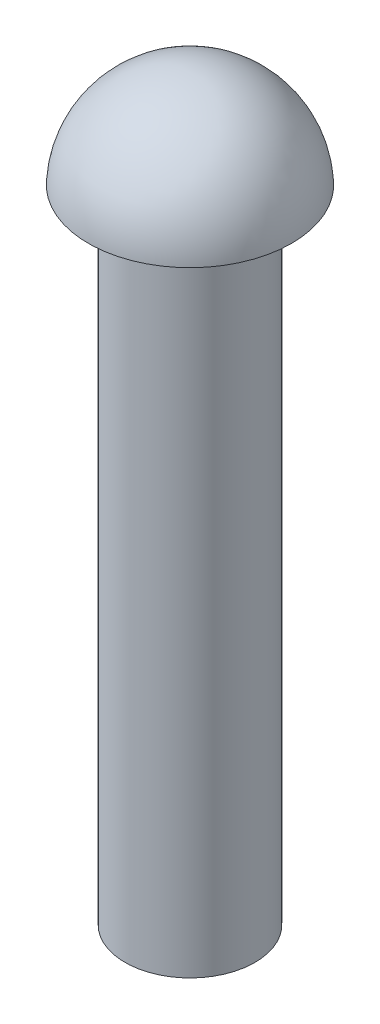
SolidWorks part; units mm, degrees
material "2.0060 (Cu-ETP)"
ref_plane "Front Plane" through (0, 0, 0) normal (0, 0, 1) x (1, 0, 0)
ref_plane "Top Plane" through (0, 0, 0) normal (0, 1, 0) x (1, 0, 0)
ref_plane "Right Plane" through (0, 0, 0) normal (1, 0, 0) x (0, 0, -1)
sketch "Sketch1" plane through (0, 0, 0) normal (0, 0, 1) x (1, 0, 0)
  line L0 (0, 0) -> (3.8608, 0)
  line L1 (3.8608, 0) -> (3.8608, 38.1)
  line L2 (3.8608, 38.1) -> (6.0399, 38.1)
  line L3 (0, 0) -> (0, 43.8912)
  arc A0 (6.0399, 38.1) -> (0, 43.8912) centre (0, 37.846) ccw
  dimension "D3" = 12.0904
  dimension "D1" = 5.7912
  dimension "D2" = 38.1
  dimension "D4" = 3.8608
revolve "Revolve1" add sketch "Sketch1" angle 360 about L3
